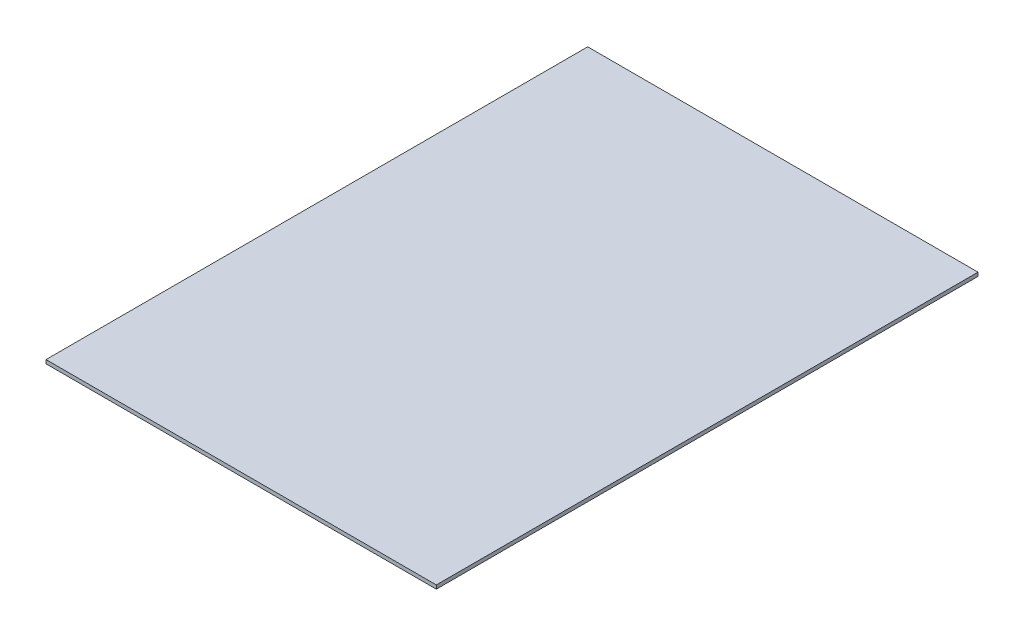
SolidWorks part; units mm, degrees
material "Custom Plastic"
ref_plane "Front" through (0, 0, 0) normal (0, 0, 1) x (1, 0, 0)
ref_plane "Top" through (0, 0, 0) normal (0, 1, 0) x (1, 0, 0)
ref_plane "Right" through (0, 0, 0) normal (1, 0, 0) x (0, 0, -1)
sketch "Sketch1" plane through (0, 0, 0) normal (0, 1, 0) x (1, 0, 0)
  line L1 (-66.83, 92.75) -> (66.83, 92.75)
  line L2 (-66.83, 92.75) -> (-66.83, -92.75)
  line L3 (-66.83, -92.75) -> (66.83, -92.75)
  line L4 (66.83, 92.75) -> (66.83, -92.75)
  line L5 (-66.83, 92.75) -> (66.83, -92.75) construction
  line L6 (-66.83, -92.75) -> (66.83, 92.75) construction
  point P0 (0, 0)
  dimension "D2" = 185.5
extrude "Boss-Extrude1" add sketch "Sketch1" along normal mid plane 1.27
